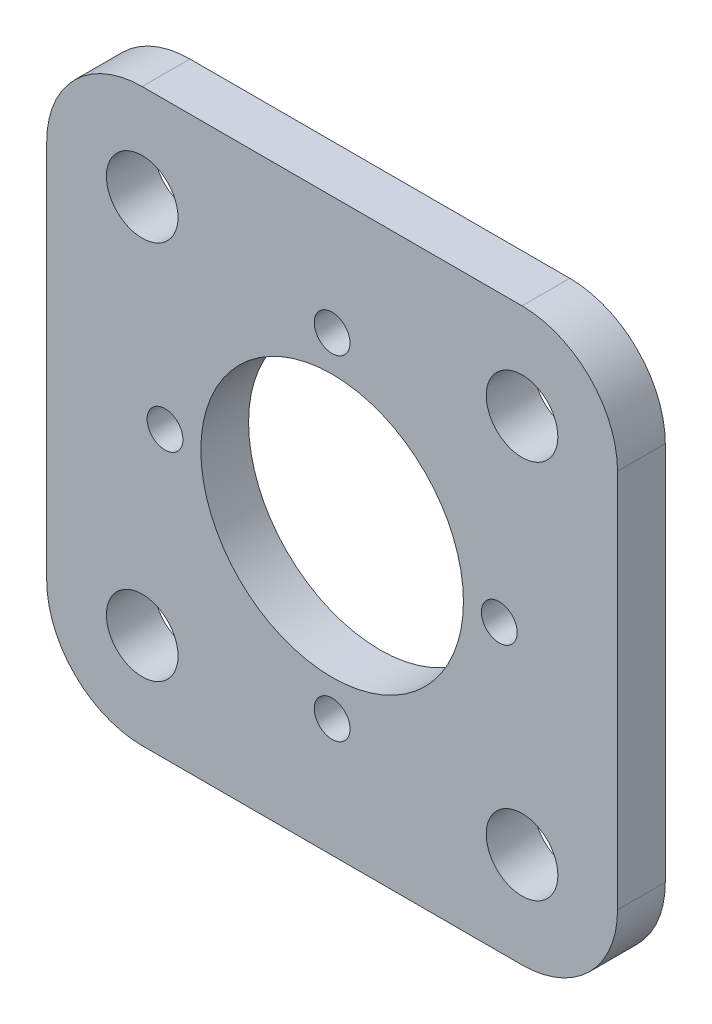
SolidWorks part; units mm, degrees
ref_plane "前视基准面" through (0, 0, 0) normal (0, 0, 1) x (1, 0, 0)
ref_plane "上视基准面" through (0, 0, 0) normal (0, 1, 0) x (1, 0, 0)
ref_plane "右视基准面" through (0, 0, 0) normal (1, 0, 0) x (0, 0, -1)
sketch "草图1" plane through (0, 0, 0) normal (0, 0, 1) x (1, 0, 0)
  line L0 (0, 0) -> (15.9099, 15.9099) construction
  line L5 (-15.9099, 23.9099) -> (15.9099, 23.9099)
  line L6 (-23.9099, 15.9099) -> (-23.9099, -15.9099)
  line L7 (-15.9099, -23.9099) -> (15.9099, -23.9099)
  line L8 (23.9099, 15.9099) -> (23.9099, -15.9099)
  circle A0 centre (0, 0) radius 14 construction
  circle A1 centre (0, 0) radius 11
  circle A2 centre (0, 14) radius 1.5
  circle A3 centre (14, 0) radius 1.5
  circle A4 centre (0, -14) radius 1.5
  circle A5 centre (-14, 0) radius 1.5
  circle A7 centre (0, 0) radius 22.5 construction
  circle A8 centre (15.9099, 15.9099) radius 3
  circle A9 centre (15.9099, -15.9099) radius 3
  circle A10 centre (-15.9099, -15.9099) radius 3
  circle A11 centre (-15.9099, 15.9099) radius 3
  arc A16 (-15.9099, 23.9099) -> (-23.9099, 15.9099) centre (-15.9099, 15.9099) ccw
  arc A17 (23.9099, 15.9099) -> (15.9099, 23.9099) centre (15.9099, 15.9099) ccw
  arc A18 (15.9099, -23.9099) -> (23.9099, -15.9099) centre (15.9099, -15.9099) ccw
  arc A19 (-23.9099, -15.9099) -> (-15.9099, -23.9099) centre (-15.9099, -15.9099) ccw
  point P15 (0, 0)
  point P26 (0, 0)
  point P33 (5.3033, -5.3033)
  point P34 (0, 0)
  dimension "D1" = 4
  dimension "D2" = 4
  dimension "D3" = 4
extrude "凸台-拉伸1" add sketch "草图1" along normal blind 4
